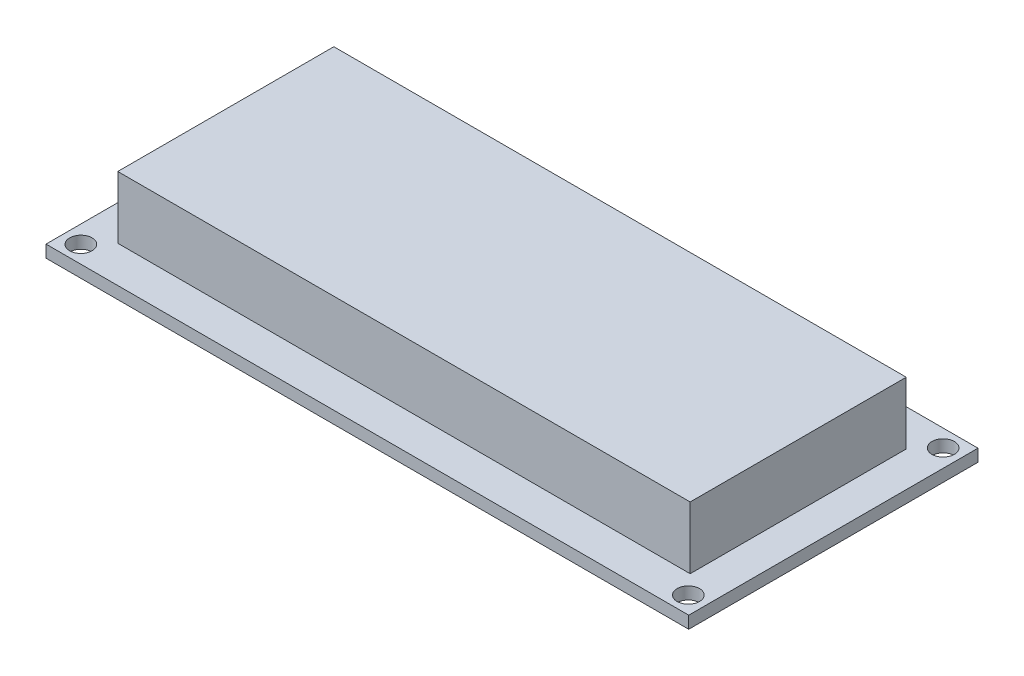
SolidWorks part; units mm, degrees
ref_plane "Front Plane" through (0, 0, 0) normal (0, 0, 1) x (1, 0, 0)
ref_plane "Top Plane" through (0, 0, 0) normal (0, 1, 0) x (1, 0, 0)
ref_plane "Right Plane" through (0, 0, 0) normal (1, 0, 0) x (0, 0, -1)
sketch "Sketch1" plane through (0, 0, 0) normal (0, 1, 0) x (1, 0, 0)
  line L1 (-40.0431, 18.0213) -> (40.0431, 18.0213)
  line L2 (-40.0431, 18.0213) -> (-40.0431, -18.0213)
  line L3 (-40.0431, -18.0213) -> (40.0431, -18.0213)
  line L4 (40.0431, 18.0213) -> (40.0431, -18.0213)
  line L5 (-40.0431, 18.0213) -> (40.0431, -18.0213) construction
  line L6 (-40.0431, -18.0213) -> (40.0431, 18.0213) construction
  point P0 (0, 0)
  dimension "D1" = 80.0862
  dimension "D2" = 36.0426
extrude "Extrude1" add sketch "Sketch1" along normal blind 1.524
sketch "Sketch2" plane through (0, 1.524, 0) normal (0, 1, 0) x (1, 0, 0)
  line L1 (-35.6616, 13.462) -> (35.6616, 13.462)
  line L2 (-35.6616, 13.462) -> (-35.6616, -13.462)
  line L3 (-35.6616, -13.462) -> (35.6616, -13.462)
  line L4 (35.6616, 13.462) -> (35.6616, -13.462)
  line L5 (-35.6616, 13.462) -> (35.6616, -13.462) construction
  line L6 (-35.6616, -13.462) -> (35.6616, 13.462) construction
  point P0 (0, 0)
  dimension "D1" = 71.3232
  dimension "D2" = 26.924
extrude "Extrude2" add sketch "Sketch2" along normal blind 7.747
sketch "Sketch3" plane through (0, 1.524, 0) normal (0, 1, 0) x (1, 0, 0)
  line L2 (0, 18.0213) -> (0, -18.0213) construction
  line L3 (40.0431, 18.0213) -> (-40.0431, 18.0213) construction
  line L4 (-40.0431, -18.0213) -> (40.0431, -18.0213) construction
  line L5 (-40.0431, 0) -> (40.0431, 0) construction
  line L6 (-40.0431, 18.0213) -> (-40.0431, -18.0213) construction
  line L7 (40.0431, -18.0213) -> (40.0431, 18.0213) construction
  circle A0 centre (-37.846, 15.875) radius 1.397
  circle A1 centre (37.846, 15.875) radius 1.397
  circle A2 centre (37.846, -15.875) radius 1.397
  circle A3 centre (-37.846, -15.875) radius 1.397
  dimension "D1" = 75.692
  dimension "D2" = 2.794
  dimension "D3" = 2.794
  dimension "D4" = 2.794
  dimension "D5" = 31.75
extrude "Extrude3" cut sketch "Sketch3" against normal through all
sketch "Sketch4" plane through (0, 1.524, 0) normal (0, 1, 0) x (1, 0, 0)
  line L0 (40.0431, 18.0213) -> (-40.0431, 18.0213) construction
  line L1 (-40.0431, 18.0213) -> (-40.0431, -18.0213) construction
  circle A0 centre (-34.3281, 15.8877) radius 0.254
  circle A1 centre (-31.7881, 15.8877) radius 0.254
  circle A2 centre (-29.2481, 15.8877) radius 0.254
  circle A3 centre (-26.7081, 15.8877) radius 0.254
  circle A4 centre (-24.1681, 15.8877) radius 0.254
  circle A5 centre (-21.6281, 15.8877) radius 0.254
  circle A6 centre (-19.0881, 15.8877) radius 0.254
  circle A7 centre (-16.5481, 15.8877) radius 0.254
  circle A8 centre (-14.0081, 15.8877) radius 0.254
  circle A9 centre (-11.4681, 15.8877) radius 0.254
  circle A10 centre (-8.9281, 15.8877) radius 0.254
  circle A11 centre (-6.3881, 15.8877) radius 0.254
  circle A12 centre (-3.8481, 15.8877) radius 0.254
  circle A13 centre (-1.3081, 15.8877) radius 0.254
  circle A14 centre (1.2319, 15.8877) radius 0.254
  circle A15 centre (3.7719, 15.8877) radius 0.254
  dimension "D1" = 0.508
  dimension "D2" = 2.1336
  dimension "D3" = 5.715
extrude "Extrude4" cut sketch "Sketch4" against normal through all
